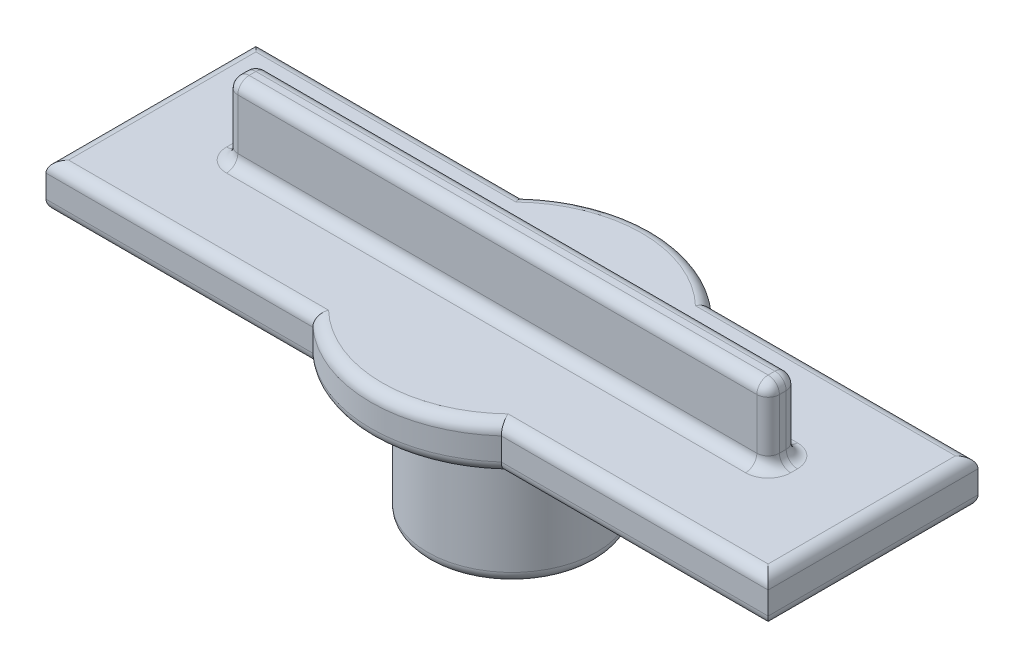
SolidWorks part; units mm, degrees
ref_plane "Front Plane" through (0, 0, 0) normal (0, 0, 1) x (1, 0, 0)
ref_plane "Top Plane" through (0, 0, 0) normal (0, 1, 0) x (1, 0, 0)
ref_plane "Right Plane" through (0, 0, 0) normal (1, 0, 0) x (0, 0, -1)
sketch "Sketch1" plane through (0, 0, 0) normal (0, 1, 0) x (1, 0, 0)
  circle A0 centre (0, 0) radius 3.175
  circle A1 centre (0, 0) radius 9.525
  dimension "D1" = 6.35
  dimension "D2" = 19.05
extrude "Boss-Extrude1" add sketch "Sketch1" along normal blind 15.24
sketch "Sketch2" plane through (0, 15.24, 0) normal (0, 1, 0) x (1, 0, 0)
  circle A0 centre (0, 0) radius 1.5875
  circle A1 centre (0, 0) radius 15.875
  dimension "D1" = 3.175
  dimension "D2" = 31.75
extrude "Boss-Extrude2" add sketch "Sketch2" along normal blind 5.08
sketch "Sketch3" plane through (0, 20.32, 0) normal (0, 1, 0) x (1, 0, 0)
  line L1 (-30.48, -1.651) -> (30.48, -1.651)
  line L2 (-30.48, -1.651) -> (-30.48, 1.651)
  line L3 (-30.48, 1.651) -> (30.48, 1.651)
  line L4 (30.48, -1.651) -> (30.48, 1.651)
  line L5 (-30.48, -1.651) -> (30.48, 1.651) construction
  line L6 (-30.48, 1.651) -> (30.48, -1.651) construction
  point P0 (0, 0)
  dimension "D1" = 3.302
  dimension "D2" = 60.96
extrude "Boss-Extrude3" add sketch "Sketch3" along normal blind 8.255
sketch "Sketch4" plane through (0, 20.32, 0) normal (0, -1, 0) x (1, 0, 0)
  line L0 (-15.7889, -1.651) -> (-30.48, -1.651) construction
  line L1 (-40.64, 11.811) -> (40.64, 11.811)
  line L2 (-40.64, 11.811) -> (-40.64, -11.811)
  line L3 (-40.64, -11.811) -> (40.64, -11.811)
  line L4 (40.64, 11.811) -> (40.64, -11.811)
  line L5 (-40.64, 11.811) -> (40.64, -11.811) construction
  line L6 (-40.64, -11.811) -> (40.64, 11.811) construction
  line L7 (-30.48, -1.651) -> (-30.48, 1.651) construction
  point P0 (0, 0)
  dimension "D1" = 10.16
  dimension "D2" = 10.16
extrude "Boss-Extrude4" add sketch "Sketch4" along normal blind 5.08
sketch "Sketch5" plane through (0, 0, 0) normal (0, -1, 0) x (1, 0, 0)
  line L0 (-1.905, 2.54) -> (1.905, 2.54)
  line L1 (-8.9803, -3.175) -> (8.9803, -3.175) construction
  circle A0 centre (0, 0) radius 3.175
  circle A1 centre (0, 0) radius 9.525 construction
  circle A2 centre (0, 0) radius 3.175 construction
  circle M5 centre (0, 0) radius 3.175
  dimension "D1" = 5.715
extrude "Boss-Extrude5" add sketch "Sketch5" against normal up to next contours L0 M5
fillet "Fillet1" radius 1.27 4 edges at (-30.48, 24.4475, 1.651) (-30.48, 24.4475, -1.651) (30.48, 24.4475, -1.651) (30.48, 24.4475, 1.651)
fillet "Fillet2" radius 1.27 8 edges at (-30.108, 28.575, 1.279) (-30.48, 28.575, 0) (-30.108, 28.575, -1.279) (0, 28.575, -1.651) (30.108, 28.575, -1.279) (30.48, 28.575, 0) (30.108, 28.575, 1.279) (0, 28.575, 1.651)
fillet "Fillet3" radius 1.27 8 edges at (25.6237, 20.32, 11.811) (0, 20.32, 15.875) (-25.6237, 20.32, 11.811) (-40.64, 20.32, 0) (-25.6237, 20.32, -11.811) (0, 20.32, -15.875) (25.6237, 20.32, -11.811) (40.64, 20.32, 0)
fillet "Fillet4" radius 1.27 8 edges at (-40.64, 15.24, 0) (-25.6237, 15.24, 11.811) (0, 15.24, 15.875) (25.6237, 15.24, 11.811) (40.64, 15.24, 0) (25.6237, 15.24, -11.811) (0, 15.24, -15.875) (-25.6237, 15.24, -11.811)
fillet "Fillet5" radius 3.81 1 edges at (0, 15.24, 9.525)
fillet "Fillet6" radius 0.635 2 edges at (0, 0, 2.54) (0, 0, -3.175)
fillet "Fillet7" radius 1.27 1 edges at (0, 0, 9.525)
fillet "Fillet8" radius 1.27 8 edges at (30.108, 20.32, -1.279) (30.48, 20.32, 0) (30.108, 20.32, 1.279) (0, 20.32, 1.651) (-30.108, 20.32, 1.279) (-30.48, 20.32, 0) (-30.108, 20.32, -1.279) (0, 20.32, -1.651)
